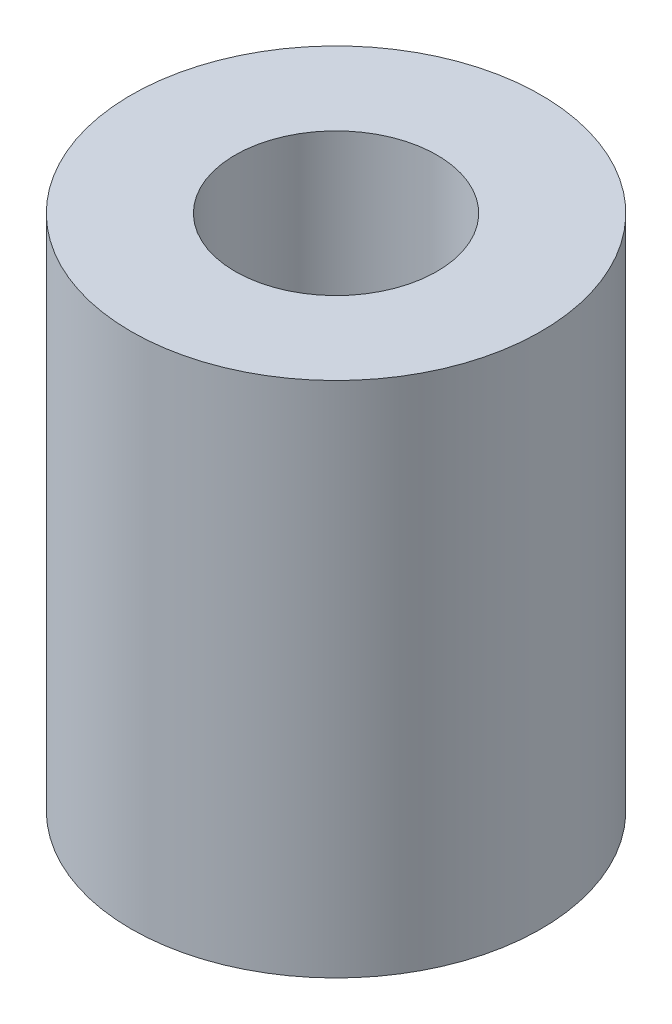
SolidWorks part; units mm, degrees
ref_plane "Alzado" through (0, 0, 0) normal (0, 0, 1) x (1, 0, 0)
ref_plane "Planta" through (0, 0, 0) normal (0, 1, 0) x (1, 0, 0)
ref_plane "Vista lateral" through (0, 0, 0) normal (1, 0, 0) x (0, 0, -1)
sketch "Croquis1" plane through (0, 0, 0) normal (0, 1, 0) x (1, 0, 0)
  circle A0 centre (0, 0) radius 4.875
  circle A1 centre (0, 0) radius 9.9
  dimension "D1" = 9.75
  dimension "D2" = 19.8
extrude "Saliente-Extruir1" add sketch "Croquis1" along normal blind 25
